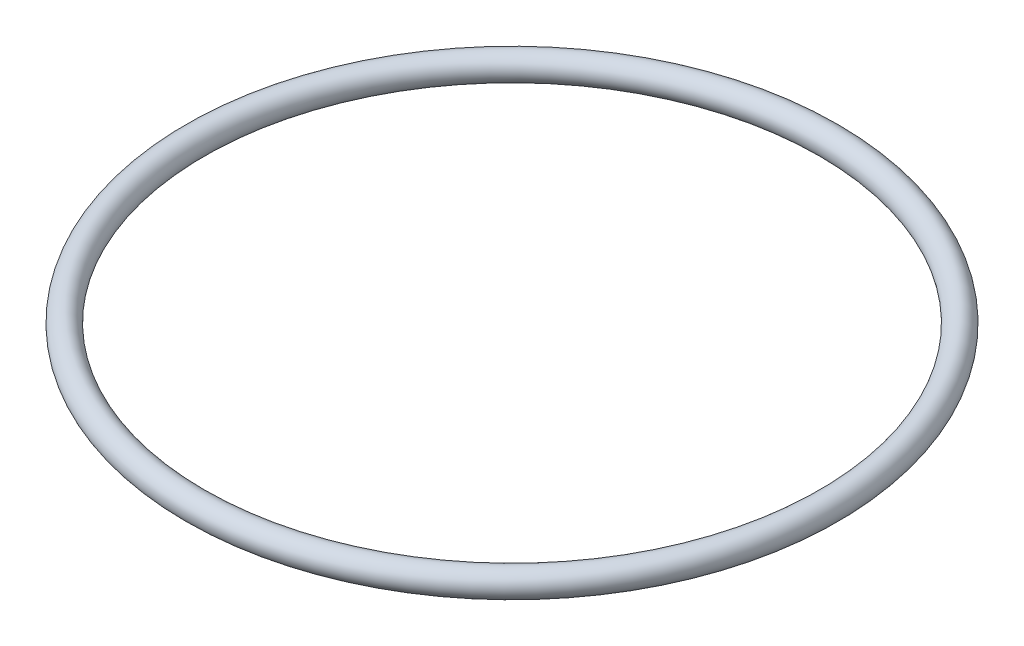
SolidWorks part; units mm, degrees
ref_plane "Front Plane" through (0, 0, 0) normal (0, 0, 1) x (1, 0, 0)
ref_plane "Top Plane" through (0, 0, 0) normal (0, 1, 0) x (1, 0, 0)
ref_plane "Right Plane" through (0, 0, 0) normal (1, 0, 0) x (0, 0, -1)
sketch "Sketch1" plane through (0, 0, 0) normal (0, 0, 1) x (1, 0, 0)
  line L0 (0, -4.681) -> (0, 13.4676) construction
  circle A0 centre (-19.43, 0.6015) radius 0.7937
  dimension "D2" = 1.5875
  dimension "D1" = 19.43
revolve "Revolve1" add sketch "Sketch1" angle 360 about L0
